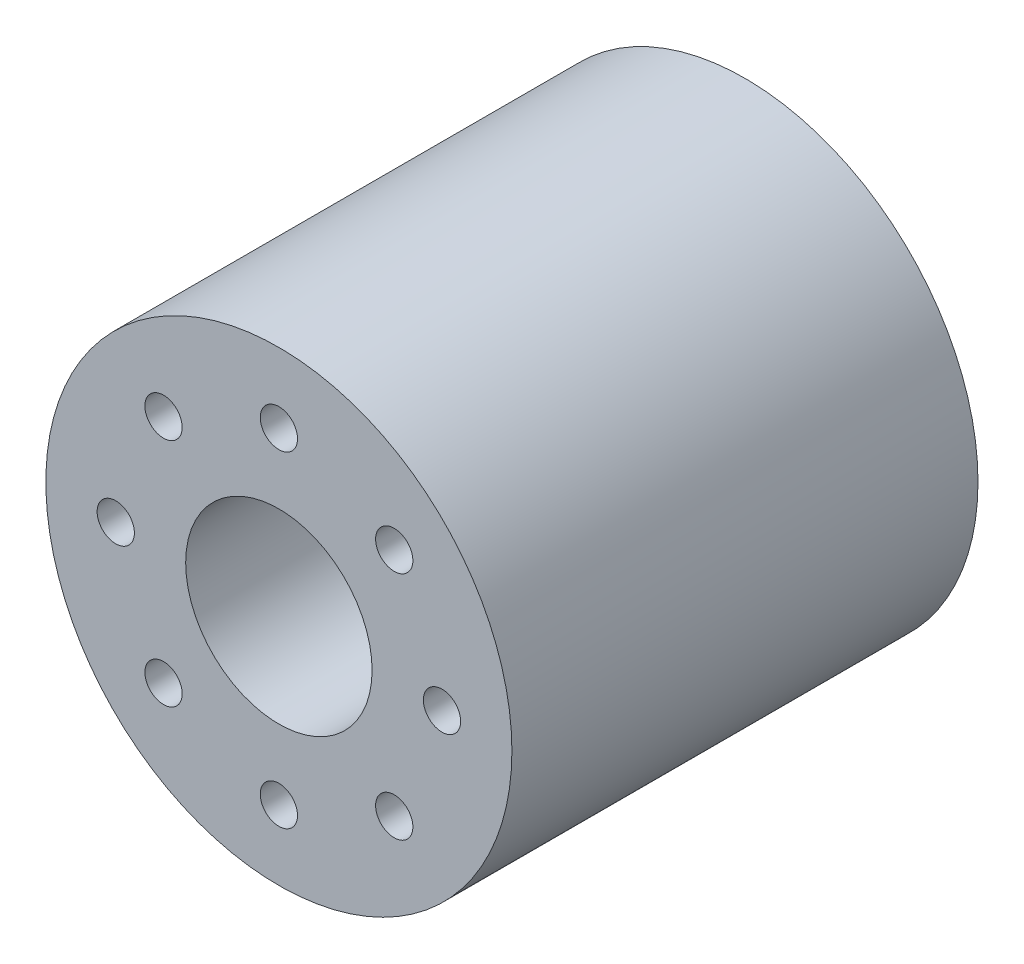
SolidWorks part; units mm, degrees
ref_plane "Ebene vorne" through (0, 0, 0) normal (0, 0, 1) x (1, 0, 0)
ref_plane "Ebene oben" through (0, 0, 0) normal (0, 1, 0) x (1, 0, 0)
ref_plane "Ebene rechts" through (0, 0, 0) normal (1, 0, 0) x (0, 0, -1)
sketch "Skizze1" plane through (0, 0, 0) normal (0, 0, 1) x (1, 0, 0)
  circle A0 centre (0, 0) radius 12.5
  circle A1 centre (0, 0) radius 5
extrude "Aufsatz-Linear austragen1" add sketch "Skizze1" along normal blind 25
sketch "Skizze2" plane through (0, 0, 25) normal (0, 0, 1) x (1, 0, 0)
  circle A0 centre (0, 8.75) radius 1
  circle A1 centre (0, 0) radius 5 construction
  circle A4 centre (6.1872, 6.1872) radius 1
  circle A5 centre (8.75, 0) radius 1
  circle A6 centre (6.1872, -6.1872) radius 1
  circle A7 centre (0, -8.75) radius 1
  circle A8 centre (-6.1872, -6.1872) radius 1
  circle A9 centre (-8.75, 0) radius 1
  circle A10 centre (-6.1872, 6.1872) radius 1
  point P21 (0, 0)
  dimension "D1" = 8.75
  dimension "D2" = 8
extrude "Schnitt-Linear austragen1" cut sketch "Skizze2" against normal blind 25
